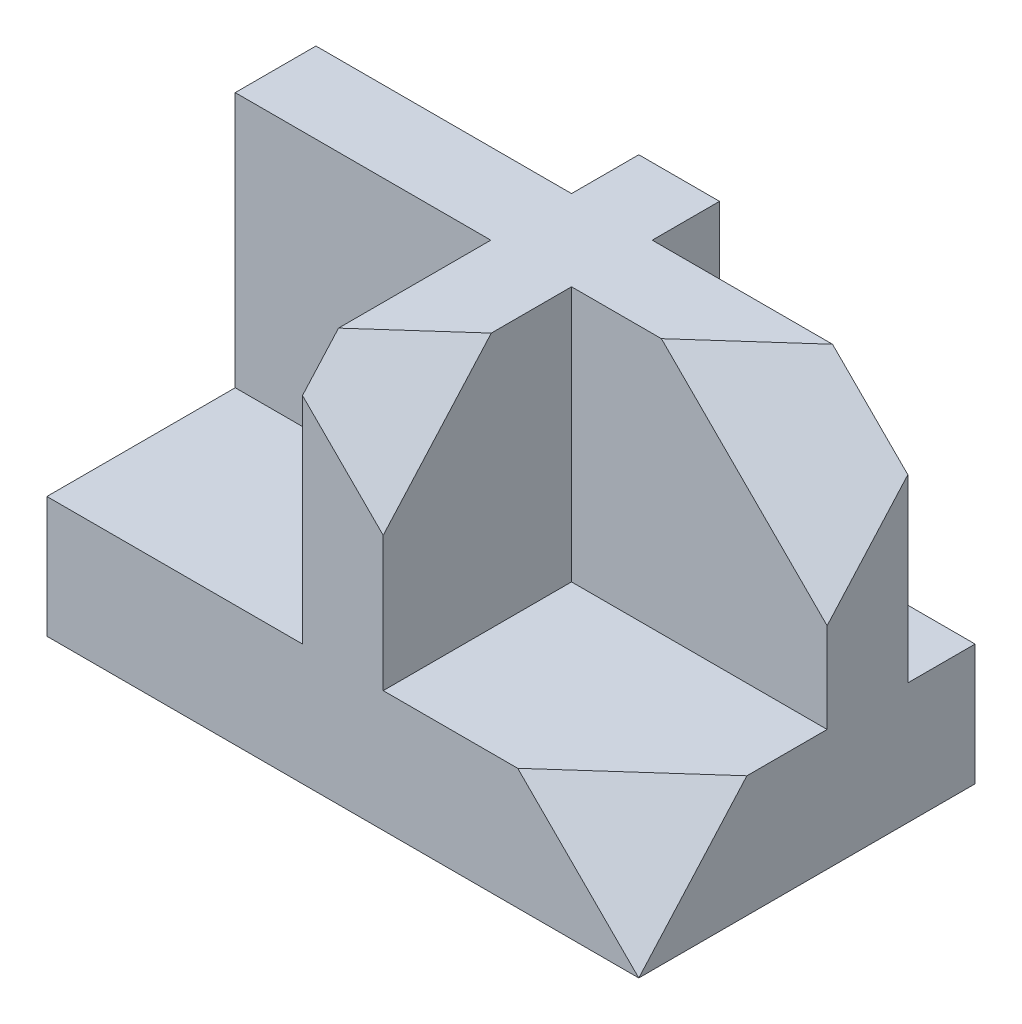
SolidWorks part; units mm, degrees
ref_plane "Front Plane" through (0, 0, 0) normal (0, 0, 1) x (1, 0, 0)
ref_plane "Top Plane" through (0, 0, 0) normal (0, 1, 0) x (1, 0, 0)
ref_plane "Right Plane" through (0, 0, 0) normal (1, 0, 0) x (0, 0, -1)
sketch "Sketch1" plane through (0, 0, 0) normal (0, 1, 0) x (1, 0, 0)
  line L1 (-44, -25) -> (44, -25)
  line L2 (-44, -25) -> (-44, 25)
  line L3 (-44, 25) -> (44, 25)
  line L4 (44, -25) -> (44, 25)
  line L5 (-44, -25) -> (44, 25) construction
  line L6 (-44, 25) -> (44, -25) construction
  point P0 (0, 0)
  dimension "D1" = 50
  dimension "D2" = 88
extrude "Boss-Extrude1" add sketch "Sketch1" along normal blind 18
sketch "Sketch2" plane through (0, 18, 0) normal (0, 1, 0) x (1, 0, 0)
  line L0 (-44, 15) -> (-6, 15)
  line L1 (-44, 25) -> (-44, -25) construction
  line L2 (-6, 15) -> (-6, 25)
  line L3 (44, 25) -> (-44, 25) construction
  line L4 (-6, 25) -> (6, 25)
  line L5 (6, 25) -> (6, 15)
  line L6 (6, 15) -> (44, 15)
  line L7 (44, -25) -> (44, 25) construction
  line L8 (44, 15) -> (44, 3)
  line L9 (44, 3) -> (6, 3)
  line L10 (6, 3) -> (6, -25)
  line L11 (-44, -25) -> (44, -25) construction
  line L12 (6, -25) -> (-6, -25)
  line L13 (-6, -25) -> (-6, 3)
  line L14 (-6, 3) -> (-44, 3)
  line L15 (-44, 3) -> (-44, 15)
  dimension "D1" = 12
  dimension "D2" = 12
  dimension "D3" = 38
  dimension "D4" = 28
extrude "Boss-Extrude2" add sketch "Sketch2" along normal blind 38
sketch "Sketch3" plane through (0, 0, 25) normal (0, 0, 1) x (1, 0, 0)
  line L0 (44, 0) -> (-12, 56) construction
  line L1 (-6, 56) -> (6, 56) construction
  line L2 (-44, 0) -> (44, 0) construction
  point P3 (-2.0995, 56)
  dimension "D1" = 45
sketch "Sketch4" plane through (44, 0, 0) normal (1, 0, 0) x (0, 0, -1)
  line L0 (-25, 0) -> (25, 56) construction
ref_plane "Plane2" through (22.1239, 22.1239, 24.7788) normal (0.5543, 0.5543, 0.6208) x (0.8323, -0.3692, -0.4135)
sketch "Sketch11" plane through (22.1239, 22.1239, 24.7788) normal (0.5543, 0.5543, 0.6208) x (0.8323, -0.3692, -0.4135)
  line L0 (-40.9995, 25.1221) -> (26.2839, 58.4229)
  line L1 (26.2839, 58.4229) -> (26.2839, -16.6504)
  line L2 (26.2839, -16.6504) -> (-40.9995, 25.1221)
extrude "Cut-Extrude1" cut sketch "Sketch11" along normal through all
